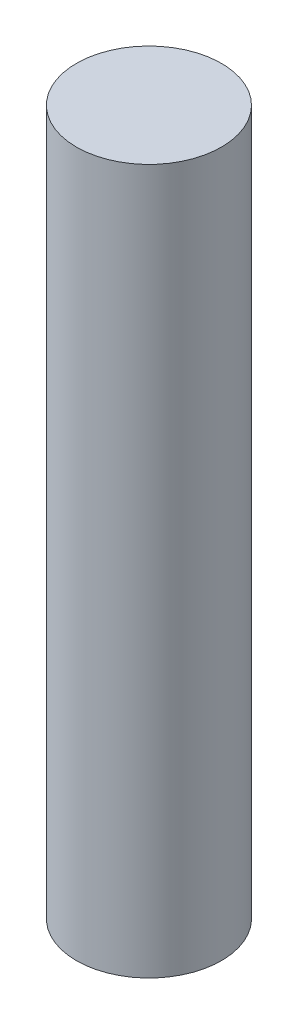
SolidWorks part; units mm, degrees
ref_plane "Plano frontal" through (0, 0, 0) normal (0, 0, 1) x (1, 0, 0)
ref_plane "Plano superior" through (0, 0, 0) normal (0, 1, 0) x (1, 0, 0)
ref_plane "Plano direito" through (0, 0, 0) normal (1, 0, 0) x (0, 0, -1)
sketch "Esboço1" plane through (0, 0, 0) normal (0, 0, 1) x (1, 0, 0)
  line L0 (1, -17) -> (-6, -17)
  line L1 (1, -17) -> (1, 51)
  line L2 (1, 51) -> (-6, 51)
  line L3 (-6, -17) -> (-6, 51)
  point P6 (-25.2695, 35.5573)
  dimension "D1" = 7
  dimension "D2" = 68
sketch "Esboço2" plane through (0, 0, 0) normal (1, 0, 0) x (0, 0, -1)
  line L0 (1, -17) -> (-6, -17)
  line L1 (1, -17) -> (1, 51)
  line L2 (1, 51) -> (-6, 51)
  line L3 (-6, -17) -> (-6, 51)
  point P6 (-25.2695, 35.5573)
  dimension "D1" = 7
  dimension "D2" = 68
revolve "Revolução2" add sketch "Esboço2" angle 360 about L3
